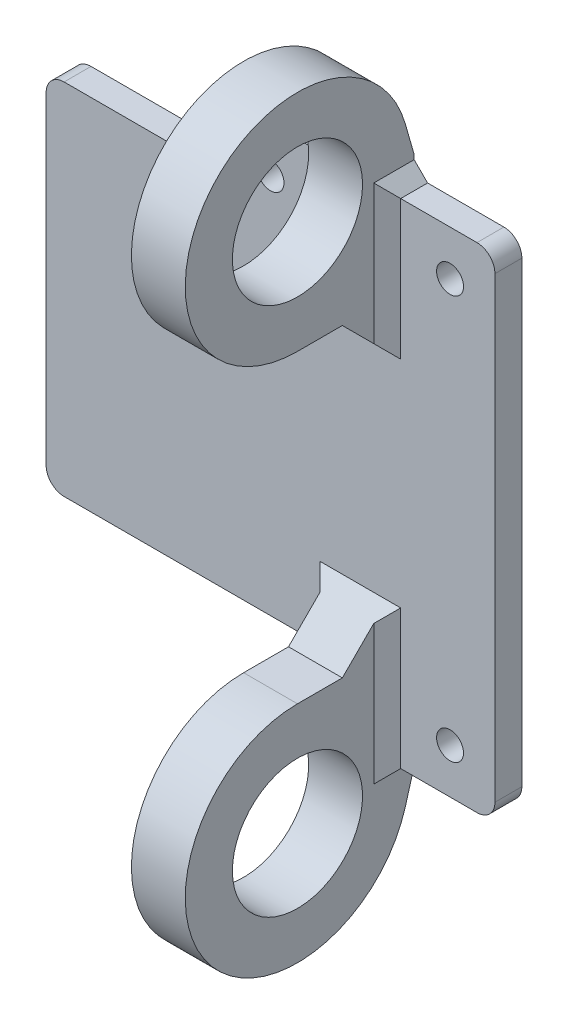
SolidWorks part; units mm, degrees
ref_plane "Front Plane" through (0, 0, 0) normal (0, 0, 1) x (1, 0, 0)
ref_plane "Top Plane" through (0, 0, 0) normal (0, 1, 0) x (1, 0, 0)
ref_plane "Right Plane" through (0, 0, 0) normal (1, 0, 0) x (0, 0, -1)
sketch "Sketch1" plane through (0, 0, 0) normal (0, 0, 1) x (1, 0, 0)
  line L0 (0, 0) -> (25, 0) construction
  line L1 (10, -27.5) -> (25, -27.5)
  line L2 (-25, -20) -> (-25, 20)
  line L3 (-5, 27.5) -> (25, 27.5)
  line L4 (25, -27.5) -> (25, 27.5)
  line L5 (25, 25.5) -> (25, -25.5) construction
  line L7 (20, 22.5) -> (20, -22.5) construction
  line L8 (-5, 27.5) -> (-5, 20)
  line L9 (-5, 20) -> (-25, 20)
  line L10 (-25, -20) -> (10, -20)
  line L11 (10, -20) -> (10, -27.5)
  line L12 (0, 0) -> (-25, 0) construction
  circle A0 centre (0, 22.5) radius 1.5
  circle A1 centre (20, 22.5) radius 1.5
  circle A2 centre (20, -22.5) radius 1.5
  point P0 (0, 0)
  point P14 (20, 0)
  point P21 (-25, 0)
  dimension "D3" = 3
  dimension "D1" = 50
  dimension "D2" = 55
  dimension "D4" = 30
  dimension "D5" = 20
  dimension "D6" = 5
  dimension "D7" = 45
  dimension "D8" = 40
  dimension "D9" = 15
extrude "Boss-Extrude1" add sketch "Sketch1" along normal blind 3
fillet "Fillet1" radius 2 4 edges at (25, 27.5, 1.5) (25, -27.5, 1.5) (-25, -20, 1.5) (-25, 20, 1.5)
sketch "Sketch2" plane through (0, 0, 0) normal (1, 0, 0) x (0, 0, -1)
  line L0 (0, 0) -> (-17.7596, 0) construction
  line L1 (-3, -25.5) -> (-3, 25.5) construction
  line L2 (-13, 17) -> (0, 17)
  line L3 (0, -25.5) -> (0, 25.5) construction
  line L4 (0, 17) -> (0, 29.5)
  line L5 (0, 29.5) -> (-0.9808, 32.9334)
  line L6 (0, -29.5) -> (-0.9808, -32.9334)
  line L7 (0, -17) -> (0, -29.5)
  line L8 (-13, -17) -> (0, -17)
  circle A0 centre (-13, 29.5) radius 7.25
  arc A1 (-0.9808, 32.9334) -> (-13, 17) centre (-13, 29.5) ccw
  circle A4 centre (-13, 29.5) radius 9 construction
  circle A5 centre (-13, -29.5) radius 9 construction
  arc A6 (-0.9808, -32.9334) -> (-13, -17) centre (-13, -29.5) cw
  circle A7 centre (-13, -29.5) radius 7.25
  dimension "D1" = 14.5
  dimension "D2" = 25
  dimension "D5" = 18
  dimension "D3" = 29.5
  dimension "D4" = 10
  dimension "D6" = 12.5
extrude "Boss-Extrude2" add sketch "Sketch2" along normal blind 6 from offset 7
chamfer "Chamfer1" distance 2 angle 45 2 edges at (-5, 20, 1.5) (-5, 27.5, 1.5)
chamfer "Chamfer2" distance 5 angle 45 2 edges at (10, -17, 3) (10, 17, 3)
chamfer "Chamfer3" distance 1.5 angle 45 8 edges at (7, -20, 1.5) (7, -16, 3) (13, -27.5, 1.5) (13, -19.75, 3) (7, 27.5, 1.5) (7, 19.75, 3) (13, 27.5, 1.5) (13, 19.75, 3)
